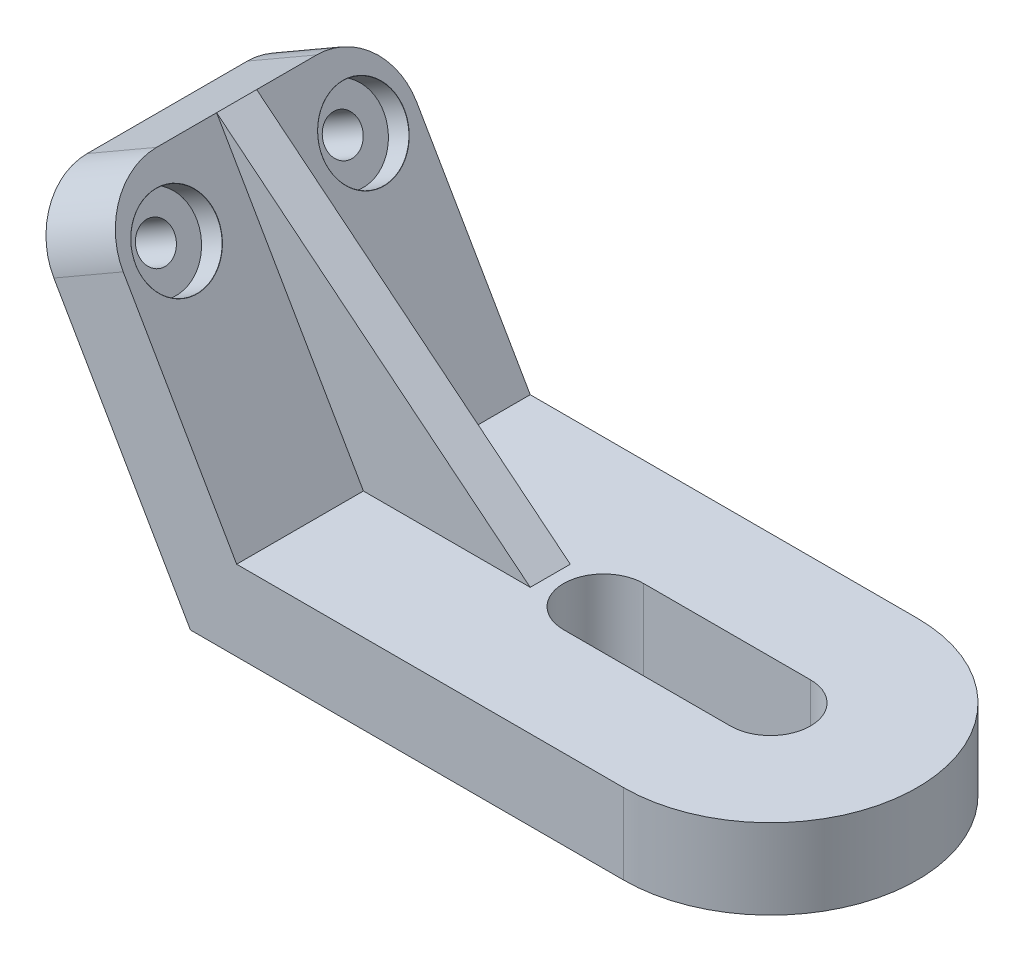
SolidWorks part; units mm, degrees
ref_plane "Front Plane" through (0, 0, 0) normal (0, 0, 1) x (1, 0, 0)
ref_plane "Top Plane" through (0, 0, 0) normal (0, 1, 0) x (1, 0, 0)
ref_plane "Right Plane" through (0, 0, 0) normal (1, 0, 0) x (0, 0, -1)
sketch "Sketch1" plane through (0, 0, 0) normal (0, 0, 1) x (1, 0, 0)
  line L0 (-41.9206, 5.5927) -> (38.0794, 5.5927)
  line L1 (38.0794, 5.5927) -> (38.0794, -6.4073)
  line L2 (38.0794, -6.4073) -> (-48.8488, -6.4073)
  line L3 (-48.8488, -6.4073) -> (-74.3129, 37.6978)
  line L4 (-41.9206, 5.5927) -> (-63.9206, 43.6978)
  line L5 (-63.9206, 43.6978) -> (-74.3129, 37.6978)
  dimension "D1" = 12
  dimension "D2" = 90
  dimension "D3" = 120
  dimension "D4" = 12
  dimension "D5" = 80
  dimension "D6" = 44
extrude "Boss-Extrude1" add sketch "Sketch1" along normal mid plane 44
hole_wizard "CBORE for M5 Hex Head Bolt1" positions "Sketch2" profile "Sketch3" counterbore size "M5" standard "ISO" end condition through all
sketch "Sketch2" plane through (-29.0188, -16.754, 0) normal (0.866, 0.5, 0) x (0, 0, -1)
  line L0 (22, 25.8037) -> (22, 69.8037) construction
  line L1 (-22, 25.8037) -> (-22, 69.8037) construction
  line L2 (-22, 69.8037) -> (22, 69.8037) construction
  point P0 (14, 59.8037)
  point P2 (-14, 59.8037)
  dimension "D1" = 8
  dimension "D2" = 8
  dimension "D3" = 10
  dimension "D4" = 10
sketch "Sketch3" plane through (-58.9206, 35.0376, -14) normal (0, 0, 1) x (-0.5, 0.866, 0)
  line L0 (0, 0) -> (0, 34.0526)
  line L1 (0, 34.0526) -> (2.75, 34.0526)
  line L3 (2.75, 34.0526) -> (2.75, 3.58)
  line L4 (6.12, 3.58) -> (2.75, 3.58)
  line L5 (6.12, 3.58) -> (6.12, 0.024)
  line L6 (6.12, 0.024) -> (6.144, 0)
  line L7 (6.144, 0) -> (0, 0)
  line L8 (-6.12, 0.024) -> (-6.144, 0) construction
  line L11 (0, -6.35) -> (0, 107.95) construction
  dimension "Thru Hole Dia." = 5.5
  dimension "Thru Hole Depth" = 34.0526
  dimension "C'Bore Dia." = 12.24
  dimension "C'Bore Depth" = 3.58
  dimension "Near C'Sink Dia." = 12.288
  dimension "Near C'Sink Angle" = 90
sketch "Sketch4" plane through (0, 0, 0) normal (0, 0, 1) x (1, 0, 0)
  line L0 (-63.9206, 43.6978) -> (-41.9206, 5.5927)
  line L1 (-41.9206, 5.5927) -> (-16.9206, 5.5927)
  line L2 (38.0794, 5.5927) -> (-41.9206, 5.5927) construction
  line L3 (-16.9206, 5.5927) -> (-63.9206, 43.6978)
  dimension "D1" = 25
extrude "Boss-Extrude2" add sketch "Sketch4" along normal mid plane 6
sketch "Sketch5" plane through (0, 5.5927, 0) normal (0, 1, 0) x (1, 0, 0)
  line L0 (-8.9206, 0) -> (16.0794, 0) construction
  line L1 (-8.9206, 6) -> (16.0794, 6)
  line L2 (-8.9206, -6) -> (16.0794, -6)
  line L3 (16.0794, 0) -> (-30.1895, 0) construction
  line L4 (-41.9206, 3) -> (-41.9206, 22) construction
  line L5 (16.0794, 0) -> (-8.9206, 0) construction
  line L6 (-8.9206, 0) -> (16.0794, 0) construction
  line L7 (38.0794, -22) -> (-41.9206, -22) construction
  line L8 (38.0794, 22) -> (-41.9206, 22) construction
  arc A0 (-8.9206, 6) -> (-8.9206, -6) centre (-8.9206, 0) ccw
  arc A1 (16.0794, -6) -> (16.0794, 6) centre (16.0794, 0) ccw
  arc A3 (16.0794, -22) -> (16.0794, 22) centre (16.0794, 0) ccw
  point P3 (3.5794, 0)
  line M9 (-41.9206, -22) -> (38.0794, -22)
  line M10 (38.0794, -22) -> (38.0794, 22)
  line M11 (38.0794, 22) -> (-41.9206, 22)
  dimension "D1" = 25
  dimension "D2" = 58
  dimension "D3" = 12
extrude "Cut-Extrude1" cut sketch "Sketch5" against normal through all contours A3 M10 M11 | A3 M9 M10 | L2 A1 L1 A0
fillet "Fillet2" radius 10 1 edges at (-69.1168, 40.6978, 22)
fillet "Fillet3" radius 10 1 edges at (-69.1168, 40.6978, -22)
